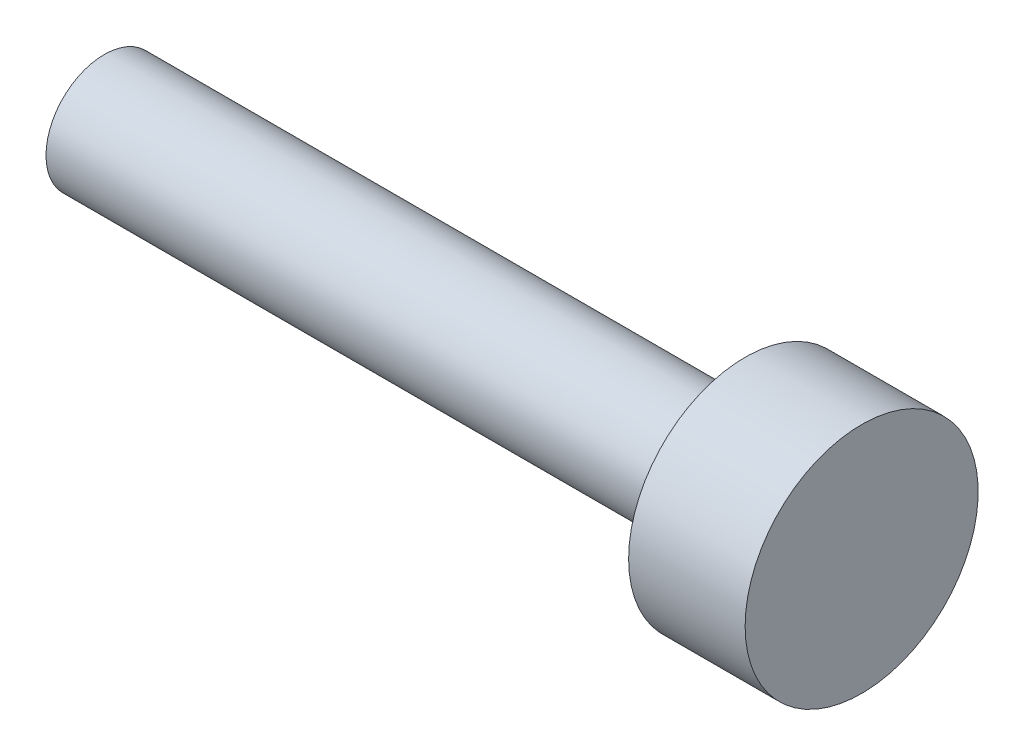
SolidWorks part; units mm, degrees
ref_plane "Front Plane" through (0, 0, 0) normal (0, 0, 1) x (1, 0, 0)
ref_plane "Top Plane" through (0, 0, 0) normal (0, 1, 0) x (1, 0, 0)
ref_plane "Right Plane" through (0, 0, 0) normal (1, 0, 0) x (0, 0, -1)
sketch "Sketch1" plane through (0, 0, 0) normal (0, 0, 1) x (1, 0, 0)
  line L0 (-116.8358, 27.1754) -> (-105.8358, 27.1754)
  line L1 (-105.8358, 27.1754) -> (-105.8358, 28.1754)
  line L2 (-105.8358, 28.1754) -> (-103.8358, 28.1754)
  line L3 (-103.8358, 28.1754) -> (-103.8358, 26.1754)
  line L4 (-116.8358, 27.1754) -> (-116.8358, 26.1754)
  line L5 (-116.8358, 26.1754) -> (-103.8358, 26.1754) construction
  line L6 (-103.8358, 26.1754) -> (-116.8358, 26.1754)
revolve "Revolve1" add sketch "Sketch1" angle 360 about L5
